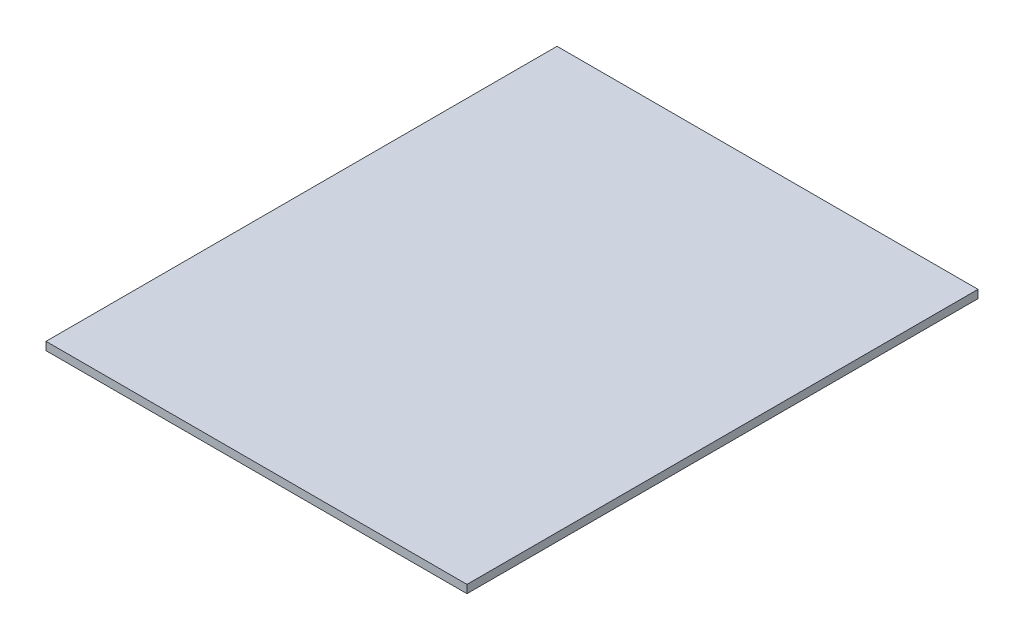
SolidWorks part; units mm, degrees
ref_plane "Front Plane" through (0, 0, 0) normal (0, 0, 1) x (1, 0, 0)
ref_plane "Top Plane" through (0, 0, 0) normal (0, 1, 0) x (1, 0, 0)
ref_plane "Right Plane" through (0, 0, 0) normal (1, 0, 0) x (0, 0, -1)
other "Configuration Table"
sketch "Sketch1" plane through (0, 0, 0) normal (0, 0, 1) x (1, 0, 0)
  line L1 (714, 1608) -> (1338, 1608)
  line L2 (714, 1608) -> (714, 1620)
  line L3 (714, 1620) -> (1338, 1620)
  line L4 (1338, 1608) -> (1338, 1620)
extrude "DET2_raf_ust_1" add sketch "Sketch1" against normal blind 757.5 separate body
